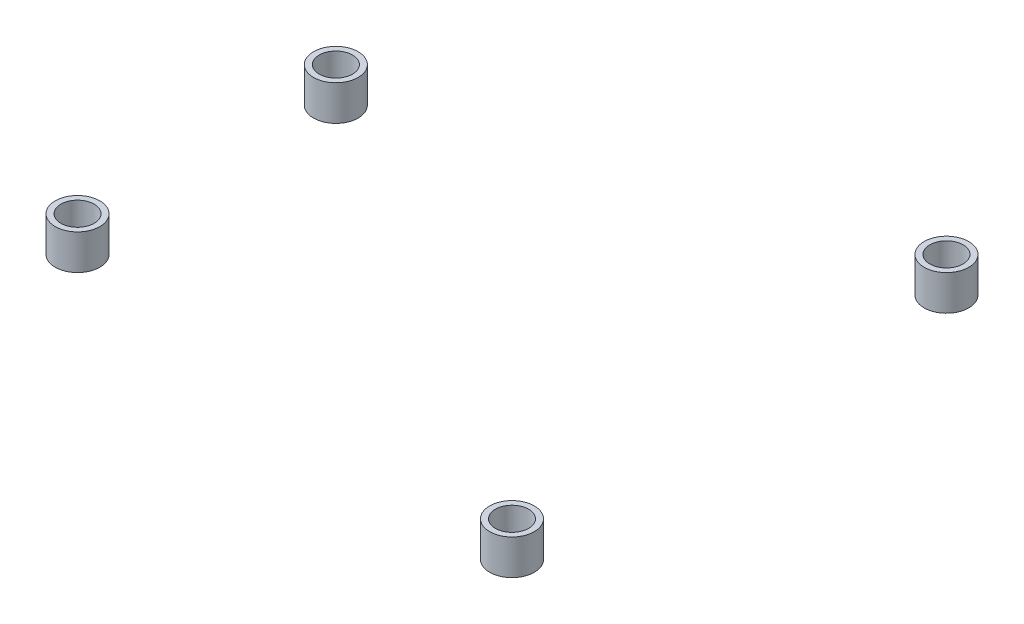
SolidWorks part; units mm, degrees
ref_plane "Front Plane" through (0, 0, 0) normal (0, 0, 1) x (1, 0, 0)
ref_plane "Top Plane" through (0, 0, 0) normal (0, 1, 0) x (1, 0, 0)
ref_plane "Right Plane" through (0, 0, 0) normal (1, 0, 0) x (0, 0, -1)
sketch "Sketch1" plane through (0, 0, 0) normal (0, 1, 0) x (1, 0, 0)
  circle A0 centre (-29.448, -17.7899) radius 1.8
  circle A1 centre (-29.448, -17.7899) radius 2.413
  circle A2 centre (-29.448, -17.7899) radius 1.8
  circle A3 centre (-29.448, 10.1501) radius 1.798
  circle A4 centre (-29.448, 10.1501) radius 2.413
  circle A5 centre (21.352, 25.3901) radius 1.798
  circle A6 centre (21.352, 25.3901) radius 2.413
  circle A7 centre (22.622, -22.8699) radius 1.798
  circle A8 centre (22.622, -22.8699) radius 2.413
  point P3 (0, 0)
  point P8 (0, 0)
  point P9 (-29.4149, 10.1387)
  point P13 (21.3281, 25.3616)
  point P14 (0, 0)
  point P18 (22.5966, -22.8443)
  line B0 (36.58, 26.8944) -> (36.5376, 27.1695)
  line B1 (36.5376, 27.1695) -> (36.453, 27.4023)
  line B2 (36.453, 27.4023) -> (36.2837, 27.6138)
  line B3 (36.2837, 27.6138) -> (36.0721, 27.7619)
  line B4 (36.0721, 27.7619) -> (35.8394, 27.8677)
  line B5 (35.8394, 27.8677) -> (35.5855, 27.9101)
  line B6 (35.5855, 27.9101) -> (-27.8921, 27.9101)
  line B7 (-27.8921, 27.9101) -> (-29.4156, 26.3866)
  line B8 (-29.4156, 26.3866) -> (-29.4156, 14.9606)
  line B9 (-29.4156, 14.9606) -> (-31.9547, 12.4215)
  line B10 (-31.9547, 12.4215) -> (-31.9547, -20.3117)
  line B11 (-31.9547, -20.3117) -> (-29.4156, -22.8508)
  line B12 (-29.4156, -22.8508) -> (-29.4156, -24.3955)
  line B13 (-29.4156, -24.3955) -> (-29.3733, -24.6494)
  line B14 (-29.3733, -24.6494) -> (-29.2886, -24.8821)
  line B15 (-29.2886, -24.8821) -> (-29.1194, -25.0937)
  line B16 (-29.1194, -25.0937) -> (-28.9077, -25.263)
  line B17 (-28.9077, -25.263) -> (-28.675, -25.3476)
  line B18 (-28.675, -25.3476) -> (-28.4211, -25.3899)
  line B19 (-28.4211, -25.3899) -> (35.5855, -25.3899)
  line B20 (35.5855, -25.3899) -> (35.8394, -25.3476)
  line B21 (35.8394, -25.3476) -> (36.0721, -25.263)
  line B22 (36.0721, -25.263) -> (36.2837, -25.0937)
  line B23 (36.2837, -25.0937) -> (36.453, -24.8821)
  line B24 (36.453, -24.8821) -> (36.5376, -24.6494)
  line B25 (36.5376, -24.6494) -> (36.58, -24.3955)
  line B26 (36.58, -24.3955) -> (36.58, 26.8944)
  circle B27 centre (-29.448, 10.1501) radius 1.8
  circle B28 centre (-29.448, -17.7899) radius 1.8
  circle B29 centre (22.622, -22.8699) radius 1.8
  circle B30 centre (21.352, 25.3901) radius 1.8
  dimension "D1" = 4.826
sketch_block_instance "Block1-1"
sketch_block "Block1"
extrude "Boss-Extrude1" add sketch "Sketch1" against normal blind 3.81 contours A4 A3 | A1 A0 | A6 A5 | A8 A7
